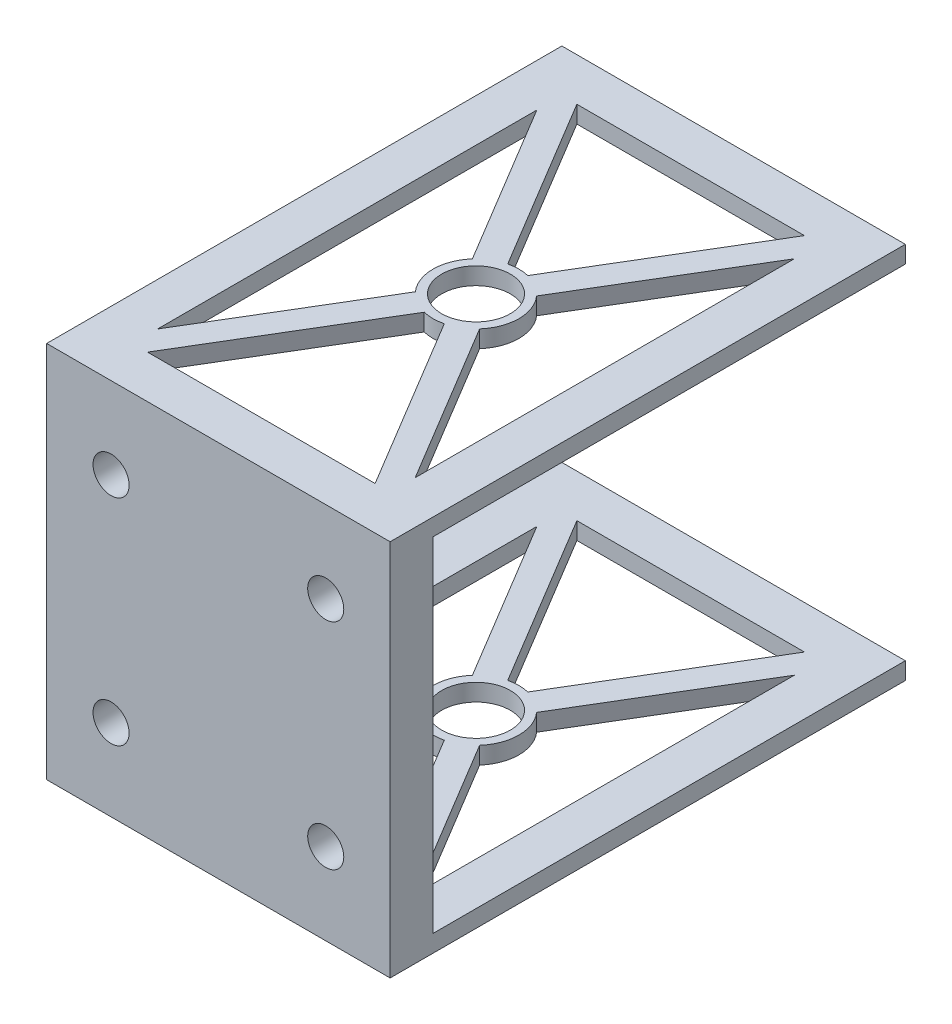
SolidWorks part; units mm, degrees
ref_plane "前视基准面" through (0, 0, 0) normal (0, 0, 1) x (1, 0, 0)
ref_plane "上视基准面" through (0, 0, 0) normal (0, 1, 0) x (1, 0, 0)
ref_plane "右视基准面" through (0, 0, 0) normal (1, 0, 0) x (0, 0, -1)
sketch "草图2" plane through (0, 0, 0) normal (0, 0, 1) x (1, 0, 0)
  line L1 (-20, 20) -> (20, 20)
  line L2 (-20, 20) -> (-20, -20)
  line L3 (-20, -20) -> (20, -20)
  line L4 (20, 20) -> (20, -20)
  line L5 (-20, 20) -> (20, -20) construction
  line L6 (-20, -20) -> (20, 20) construction
  point P0 (0, 0)
  dimension "D1" = 40
extrude "凸台-拉伸1" add sketch "草图2" along normal blind 5
sketch "草图3" plane through (0, 20, 0) normal (0, 1, 0) x (1, 0, 0)
  line L0 (20, -5) -> (-20, -5) construction
  line L2 (20, 0) -> (20, 55)
  line L3 (20, 55) -> (-20, 55)
  line L4 (-20, 0) -> (-20, 55)
  line L5 (-20, -5) -> (-20, 0) construction
  line L10 (20, 0) -> (-20, 0)
  line L11 (-20, 0) -> (-20, -5)
  line L12 (-20, -5) -> (20, -5)
  line L13 (20, -5) -> (20, 0)
  line L15 (-20, 0) -> (-20, -5)
  line L16 (-20, -5) -> (20, -5)
  line L17 (20, -5) -> (20, 0)
  dimension "D1" = 60
  dimension "D2" = 0
extrude "凸台-拉伸2" add sketch "草图3" along normal blind 2
mirror "镜向1" about plane through (0, 0, 0) normal (0, 1, 0) of "凸台-拉伸2"
sketch "草图5" plane through (0, 0, 5) normal (0, 0, 1) x (1, 0, 0)
  line L1 (-12.5, 12.5) -> (12.5, 12.5)
  line L2 (-12.5, 12.5) -> (-12.5, -12.5)
  line L3 (-12.5, -12.5) -> (12.5, -12.5)
  line L4 (12.5, 12.5) -> (12.5, -12.5)
  line L5 (-12.5, 12.5) -> (12.5, -12.5) construction
  line L6 (-12.5, -12.5) -> (12.5, 12.5) construction
  point P0 (0, 0)
  dimension "D1" = 25
hole_wizard "M5 螺纹孔1" positions "3D草图1" profile "草图6" tap size "M5" standard "GB"
sketch3d "3D草图1"
  point P0 (-12.5, 12.5, 5)
  point P3 (12.5, 12.5, 5)
  point P6 (12.5, -12.5, 5)
  point P9 (-12.5, -12.5, 5)
sketch "草图6" plane through (-12.5, 12.5, 5) normal (1, 0, 0) x (0, -1, 0)
  line L0 (0, 0) -> (0, 13.6618)
  line L1 (0, 13.6618) -> (2.1, 12.4)
  line L2 (2.1, 12.4) -> (2.1, 0)
  line L5 (2.1, 0) -> (0, 0)
  line L10 (0, 13.6618) -> (-2.1, 12.4) construction
  line L11 (0, -6.35) -> (0, 107.95) construction
  dimension "螺纹孔钻头直径" = 4.2
  dimension "螺纹孔钻头深度" = 12.4
  dimension "导头角度" = 118
cosmetic thread "孔螺蚊线1" parameters "D1"=5, "D2"=5
cosmetic thread "孔螺蚊线2" parameters "D1"=5, "D2"=5
cosmetic thread "孔螺蚊线3" parameters "D1"=5, "D2"=5
cosmetic thread "孔螺蚊线4" parameters "D1"=5, "D2"=5
sketch "草图4" plane through (0, -22, 0) normal (0, 1, 0) x (1, 0, 0)
  line L1 (-15, 50) -> (15, 50)
  line L2 (-15, 50) -> (-15, 0)
  line L3 (-15, 0) -> (15, 0)
  line L4 (15, 50) -> (15, 0)
  line L5 (-15, 50) -> (15, 0) construction
  line L6 (-15, 0) -> (15, 50) construction
  line L8 (0, 25) -> (0, 0) construction
  line L9 (20, 55) -> (-20, 55) construction
  line L10 (20, -5) -> (20, 55) construction
  line L11 (-20, -5) -> (20, -5) construction
  line L14 (-13.2507, 0) -> (-1.1677, 20.1383)
  line L15 (-15, 47.0845) -> (-3.7402, 28.3182)
  line L16 (-15, 2.9155) -> (-3.7402, 21.6818)
  line L17 (-13.2507, 50) -> (-1.1677, 29.8617)
  line L19 (-13.7138, 50.7717) -> (16.2862, 0.7717) construction
  line L21 (-16.2862, 49.2283) -> (13.7138, -0.7717) construction
  line L22 (3.7402, 28.3182) -> (15, 47.0845)
  line L23 (-13.7138, -0.7717) -> (16.2862, 49.2283) construction
  line L24 (1.1677, 29.8617) -> (13.2507, 50)
  line L25 (-16.2862, 0.7717) -> (13.7138, 50.7717) construction
  line L26 (3.7402, 21.6818) -> (15, 2.9155)
  line L27 (1.1677, 20.1383) -> (13.2507, 0)
  circle A0 centre (0, 25) radius 5
  circle A1 centre (0, 25) radius 4
  point P0 (0, 25)
  dimension "D4" = 8
  dimension "D5" = 10
  dimension "D1" = 5
  dimension "D2" = 5
  dimension "D3" = 5
  dimension "D6" = 1.5
  dimension "D8" = 1.5
  dimension "D9" = 1.5
  dimension "D7" = 1.5
extrude "切除-拉伸5" cut sketch "草图4" against normal through all and the other way through all contours L24 A0 L17 L1 | L26 A0 L22 L4 | L15 A0 L16 L2 | L14 A0 L27 L3 | A1
